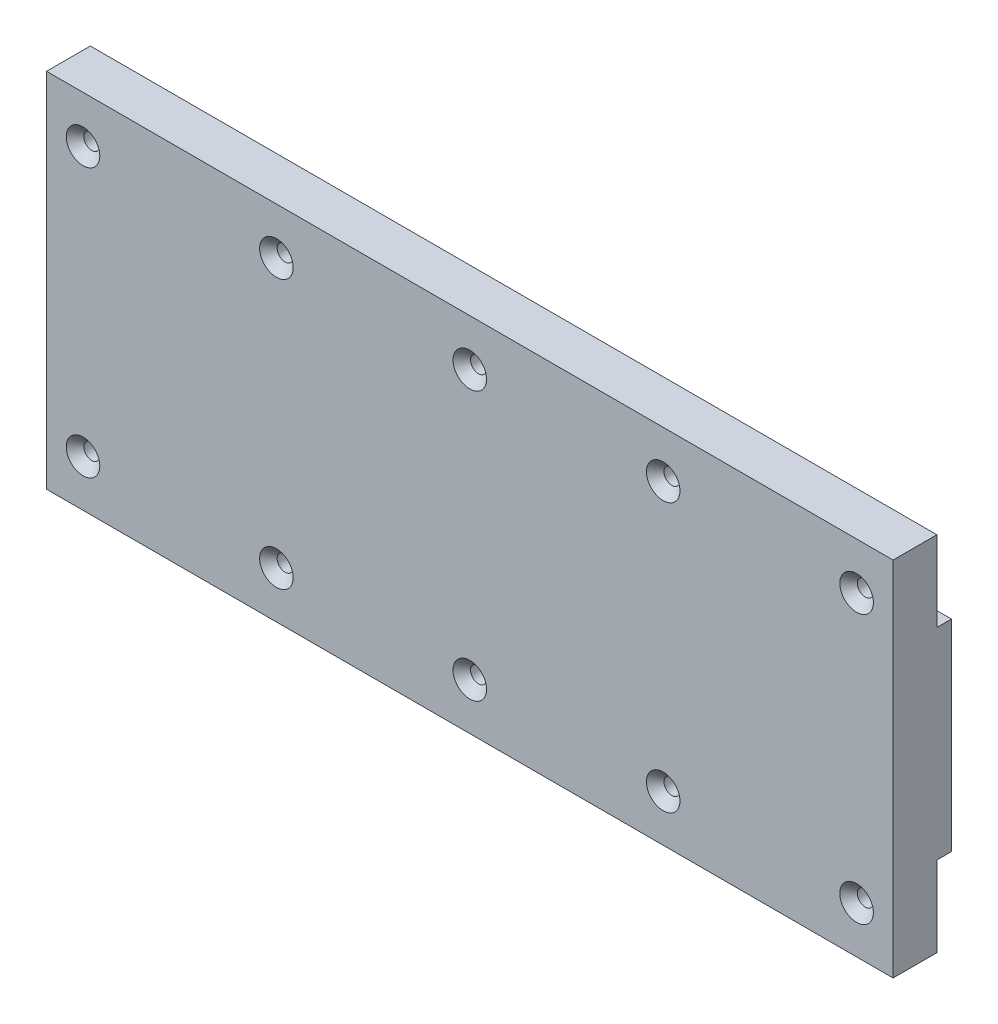
SolidWorks part; units mm, degrees
ref_plane "Alzado" through (0, 0, 0) normal (0, 0, 1) x (1, 0, 0)
ref_plane "Planta" through (0, 0, 0) normal (0, 1, 0) x (1, 0, 0)
ref_plane "Vista lateral" through (0, 0, 0) normal (1, 0, 0) x (0, 0, -1)
sketch "Croquis1" plane through (0, 0, 0) normal (1, 0, 0) x (0, 0, -1)
  line L0 (0, 0) -> (30, 0)
  line L1 (30, 0) -> (30, 55)
  line L2 (30, 55) -> (40, 55)
  line L3 (40, 55) -> (40, 193)
  line L4 (40, 193) -> (30, 193)
  line L5 (30, 193) -> (30, 248)
  line L6 (30, 248) -> (0, 248)
  line L7 (0, 248) -> (0, 0)
  point P3 (40, 124)
  point P10 (0, 124)
  dimension "D1" = 138
  dimension "D2" = 40
  dimension "D3" = 10
  dimension "D4" = 248
extrude "Saliente-Extruir1" add sketch "Croquis1" along normal blind 580
sketch "Croquis2" plane through (0, 0, 0) normal (0, 0, 1) x (1, 0, 0)
  line L0 (0, 248) -> (0, 0) construction
  line L1 (580, 0) -> (0, 0) construction
  circle A0 centre (25, 216) radius 5.5
  circle A1 centre (25, 32) radius 5.5
  circle A2 centre (157.5, 216) radius 5.5
  circle A3 centre (157.5, 32) radius 5.5
  circle A4 centre (290, 216) radius 5.5
  circle A5 centre (290, 32) radius 5.5
  circle A6 centre (422.5, 216) radius 5.5
  circle A7 centre (422.5, 32) radius 5.5
  circle A8 centre (555, 216) radius 5.5
  circle A9 centre (555, 32) radius 5.5
  dimension "D1" = 11
  dimension "D2" = 184
  dimension "D4" = 32
  dimension "D5" = 5
  dimension "D6" = 132.5
  dimension "D3" = 25
extrude "Cortar-Extruir1" cut sketch "Croquis2" against normal up to next
chamfer "Chaflán1" distance 6 angle 45 10 edges at (30.5, 32, 0) (163, 32, 0) (295.5, 32, 0) (428, 32, 0) (560.5, 32, 0) (560.5, 216, 0) (428, 216, 0) (295.5, 216, 0) (163, 216, 0) (30.5, 216, 0)
